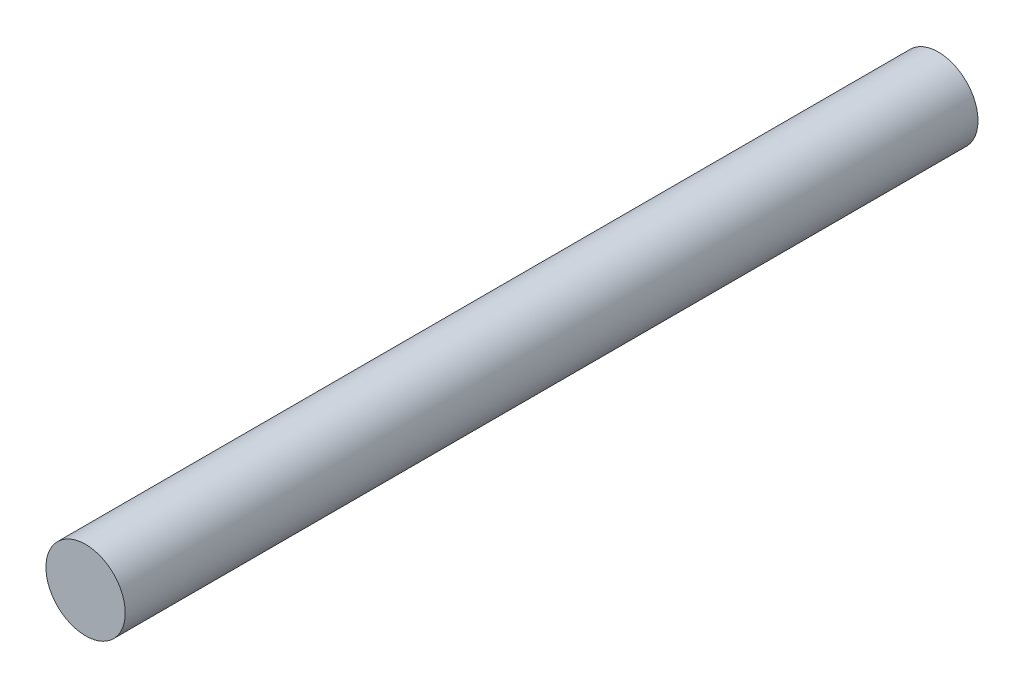
SolidWorks part; units mm, degrees
ref_plane "Front Plane" through (0, 0, 0) normal (0, 0, 1) x (1, 0, 0)
ref_plane "Top Plane" through (0, 0, 0) normal (0, 1, 0) x (1, 0, 0)
ref_plane "Right Plane" through (0, 0, 0) normal (1, 0, 0) x (0, 0, -1)
sketch "Sketch1" plane through (0, 0, 0) normal (0, 0, 1) x (1, 0, 0)
  circle A0 centre (0, 0) radius 2
  dimension "D1" = 4
extrude "Boss-Extrude1" add sketch "Sketch1" along normal blind 43
